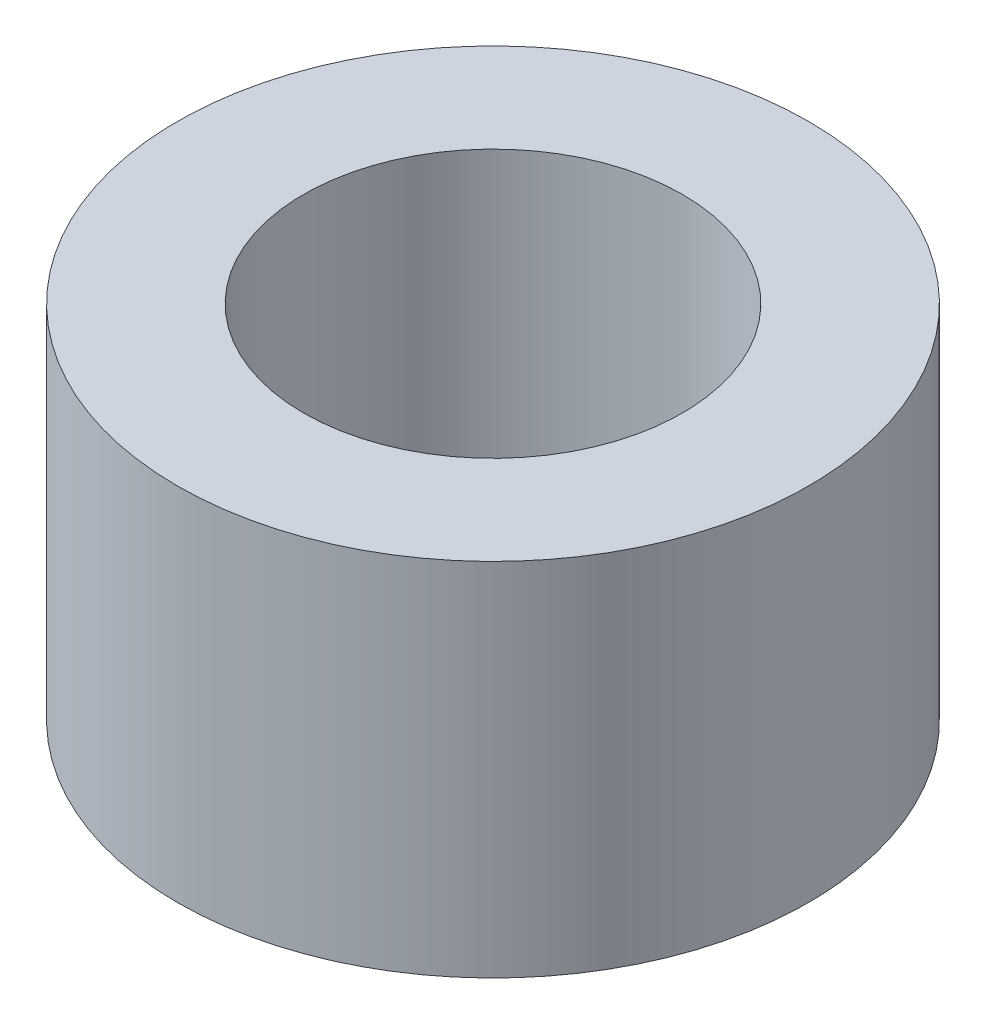
SolidWorks part; units mm, degrees
ref_plane "前视基准面" through (0, 0, 0) normal (0, 0, 1) x (1, 0, 0)
ref_plane "上视基准面" through (0, 0, 0) normal (0, 1, 0) x (1, 0, 0)
ref_plane "右视基准面" through (0, 0, 0) normal (1, 0, 0) x (0, 0, -1)
other "Configuration Table"
sketch "草图1" plane through (0, 0, 0) normal (0, 1, 0) x (1, 0, 0)
  circle A0 centre (0, 0) radius 3.5
  circle A1 centre (0, 0) radius 2.1
  dimension "D1" = 4.2
  dimension "D2" = 7
extrude "凸台-拉伸1" add sketch "草图1" along normal blind 4
